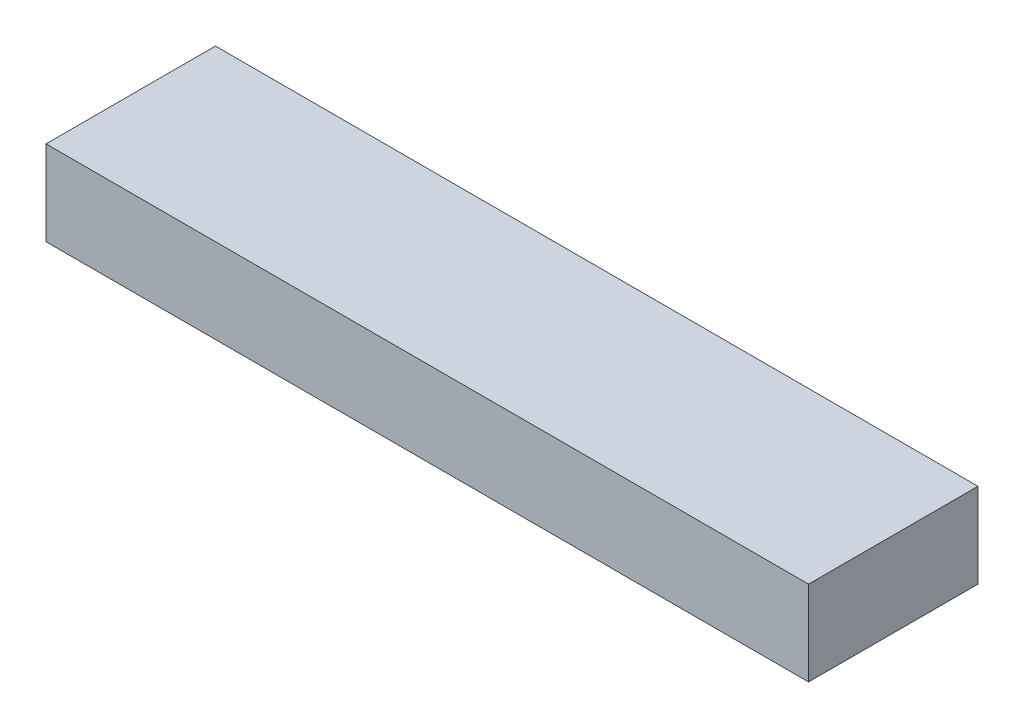
SolidWorks part; units mm, degrees
ref_plane "Front Plane" through (0, 0, 0) normal (0, 0, 1) x (1, 0, 0)
ref_plane "Top Plane" through (0, 0, 0) normal (0, 1, 0) x (1, 0, 0)
ref_plane "Right Plane" through (0, 0, 0) normal (1, 0, 0) x (0, 0, -1)
sketch "Sketch3" plane through (0, 0, 0) normal (0, 1, 0) x (1, 0, 0)
  line L1 (-225, -50) -> (225, -50)
  line L2 (-225, -50) -> (-225, 50)
  line L3 (-225, 50) -> (225, 50)
  line L4 (225, -50) -> (225, 50)
  line L5 (-225, -50) -> (225, 50) construction
  line L6 (-225, 50) -> (225, -50) construction
  point P0 (0, 0)
  dimension "D1" = 450
  dimension "D2" = 100
extrude "Boss-Extrude1" add sketch "Sketch3" along normal blind 50
